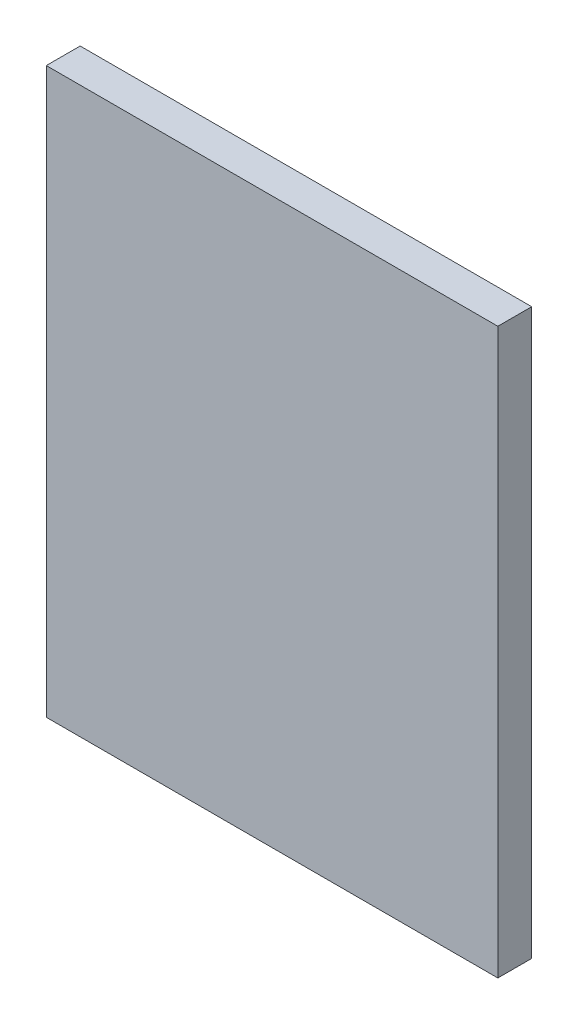
SolidWorks part; units mm, degrees
ref_plane "Front Plane" through (0, 0, 0) normal (0, 0, 1) x (1, 0, 0)
ref_plane "Top Plane" through (0, 0, 0) normal (0, 1, 0) x (1, 0, 0)
ref_plane "Right Plane" through (0, 0, 0) normal (1, 0, 0) x (0, 0, -1)
sketch "Sketch1" plane through (0, 0, 0) normal (0, 0, 1) x (1, 0, 0)
  line L1 (-40, 50) -> (40, 50)
  line L2 (-40, 50) -> (-40, -50)
  line L3 (-40, -50) -> (40, -50)
  line L4 (40, 50) -> (40, -50)
  line L5 (-40, 50) -> (40, -50) construction
  line L6 (-40, -50) -> (40, 50) construction
  point P0 (0, 0)
  dimension "D1" = 80
  dimension "D2" = 100
extrude "Boss-Extrude1" add sketch "Sketch1" along normal blind 6
